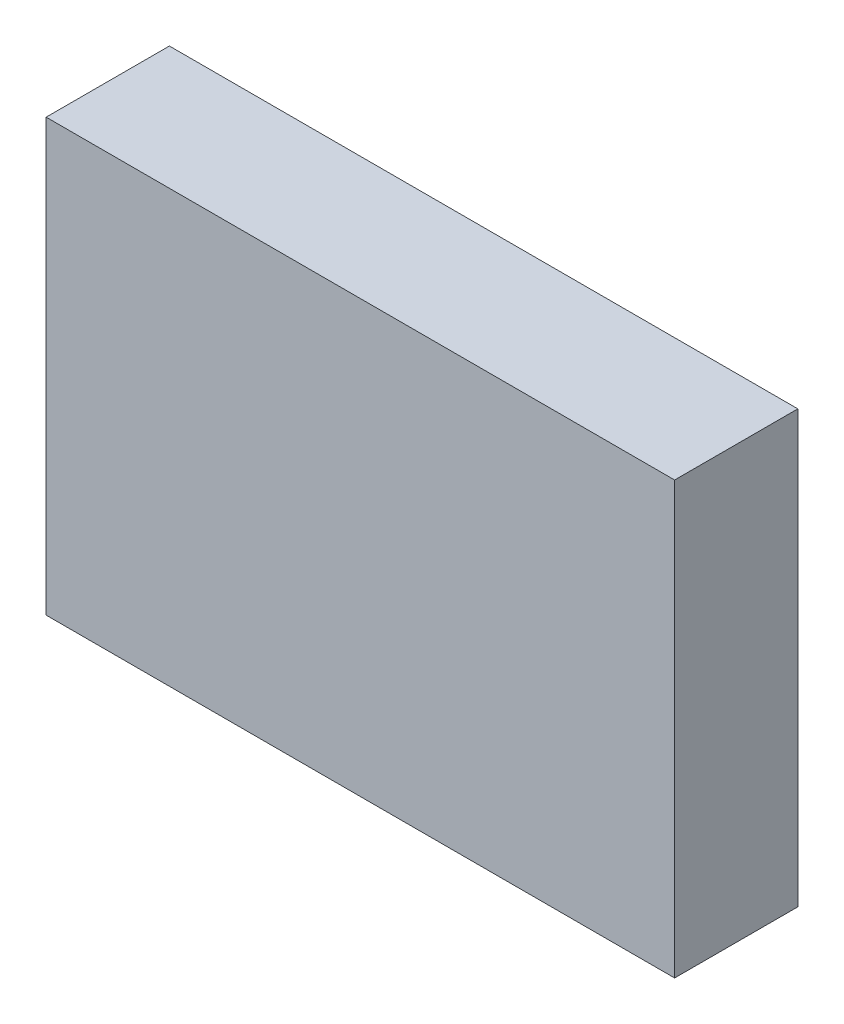
SolidWorks part; units mm, degrees
ref_plane "Front Plane" through (0, 0, 0) normal (0, 0, 1) x (1, 0, 0)
ref_plane "Top Plane" through (0, 0, 0) normal (0, 1, 0) x (1, 0, 0)
ref_plane "Right Plane" through (0, 0, 0) normal (1, 0, 0) x (0, 0, -1)
sketch "Sketch1" plane through (0, 0, 0) normal (0, 0, 1) x (1, 0, 0)
  line L1 (0, 0) -> (25.5, 0)
  line L2 (0, 0) -> (0, -17.5)
  line L3 (0, -17.5) -> (25.5, -17.5)
  line L4 (25.5, 0) -> (25.5, -17.5)
extrude "Boss-Extrude1" add sketch "Sketch1" along normal blind 5
